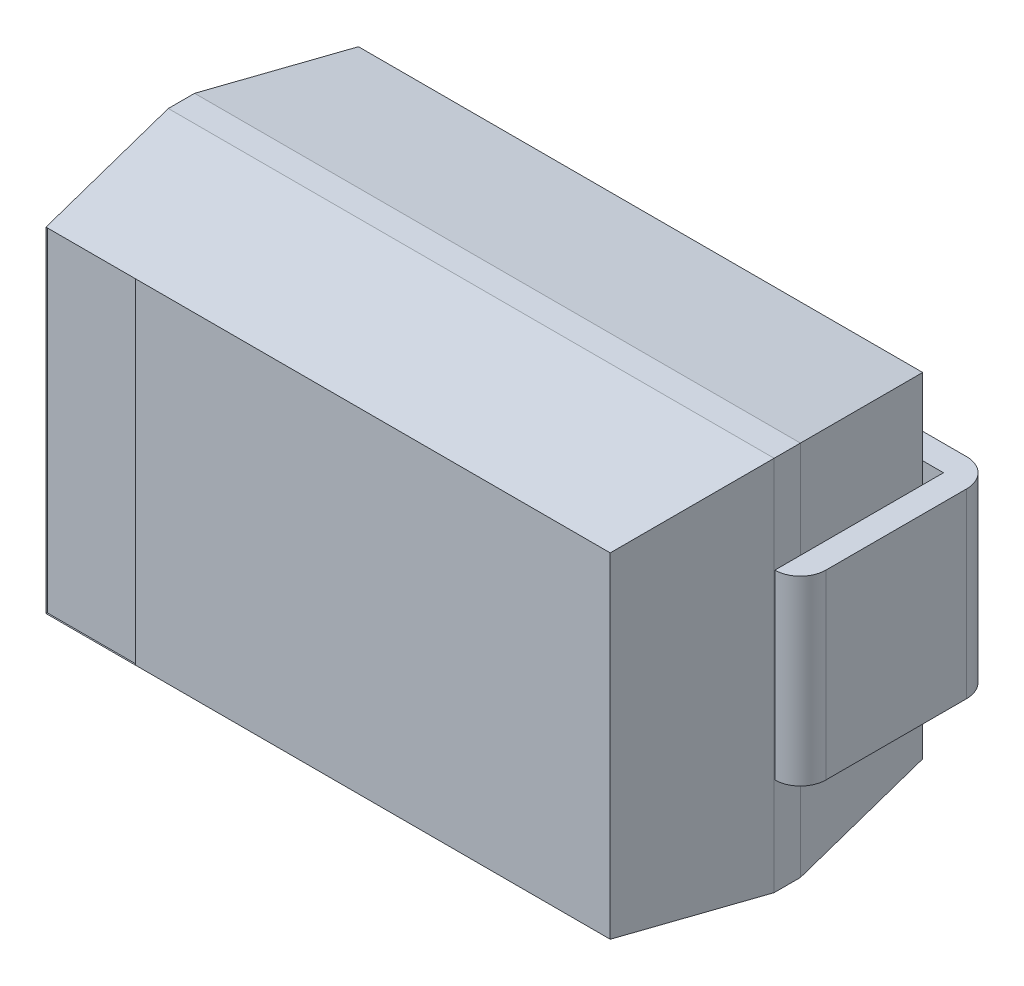
SolidWorks part; units mm, degrees
other "Детальный элемент1"
ref_plane "Спереди" through (0, 0, 0) normal (0, 0, 1) x (1, 0, 0)
ref_plane "Сверху" through (0, 0, 0) normal (0, 1, 0) x (1, 0, 0)
ref_plane "Справа" through (0, 0, 0) normal (1, 0, 0) x (0, 0, -1)
ref_plane "Плоскость1" through (0, 0, 0.2) normal (0, 0, 1) x (1, 0, 0)
sketch "Эскиз1" plane through (0, 0, 0.2) normal (0, 0, 1) x (1, 0, 0)
  line L1 (-2.375, 1.475) -> (2.375, 1.475)
  line L2 (-2.375, 1.475) -> (-2.375, -1.475)
  line L3 (-2.375, -1.475) -> (2.375, -1.475)
  line L4 (2.375, 1.475) -> (2.375, -1.475)
  line L5 (-2.375, 1.475) -> (2.375, -1.475) construction
  line L6 (-2.375, -1.475) -> (2.375, 1.475) construction
  point P0 (0, 0)
  dimension "D1" = 4.75
  dimension "D2" = 2.95
extrude "Бобышка-Вытянуть1" add sketch "Эскиз1" along normal blind 2.45
chamfer "Фаска1" distance 1.122 distance2 0.163 4 edges at (0, 1.475, 2.65) (2.375, 0, 2.65) (0, -1.475, 2.65) (-2.375, 0, 2.65)
chamfer "Фаска2" distance 0.163 distance2 1.122 4 edges at (2.375, 0, 0.2) (0, 1.475, 0.2) (0, -1.475, 0.2) (-2.375, 0, 0.2)
sketch "Эскиз2" plane through (0, 0, 0) normal (0, 1, 0) x (1, 0, 0)
  line L0 (-2.375, -0.2) -> (-2.375, -1.322)
  line L1 (-1.44, 0) -> (-2.355, 0)
  line L2 (-1.44, 0) -> (-1.44, -0.2)
  line L3 (-1.44, -0.2) -> (-2.375, -0.2)
  line L4 (-2.375, -1.322) -> (-2.375, -1.522)
  line L5 (-2.575, -1.322) -> (-2.575, -0.22)
  arc A2 (-2.375, -1.522) -> (-2.575, -1.322) centre (-2.375, -1.322) cw
  arc A3 (-2.355, 0) -> (-2.575, -0.22) centre (-2.355, -0.22) ccw
  point P0 (0, 0)
  point P4 (-2.5375, -1.1156)
  point P15 (-2.632, -0.7644)
  point P18 (-2.632, -0.7644)
  point P19 (0, 0)
  point P20 (-3.0426, -0.3256)
  point P21 (-3.076, -0.9102)
  point P22 (-3.0904, -0.8233)
  point P23 (0, 0)
  point P25 (0, 0)
  point P27 (-2.8195, -0.2)
  point P28 (-2.4847, -0.2)
  dimension "D3" = 0.22
  dimension "D1" = 0.2
  dimension "D2" = 0.2
  dimension "D4" = 0.915
extrude "Бобышка-Вытянуть2" add sketch "Эскиз2" along normal blind 0.7125 and the other way blind 0.7125 separate body
mirror "Зеркальное отражение1" about plane through (0, 0, 0) normal (1, 0, 0) of bodies 108
sketch "Эскиз3" plane through (0, 0, 2.65) normal (0, 0, 1) x (1, 0, 0)
  line L0 (2.212, 1.312) -> (-2.212, 1.312) construction
  line L1 (-2.212, -1.312) -> (-1.512, -1.312)
  line L2 (-2.212, -1.312) -> (-2.212, 1.312)
  line L3 (-2.212, 1.312) -> (-1.512, 1.312)
  line L4 (-1.512, -1.312) -> (-1.512, 1.312)
  dimension "D1" = 0.7
extrude "Вырез-Вытянуть1" cut sketch "Эскиз3" against normal blind 0.01
